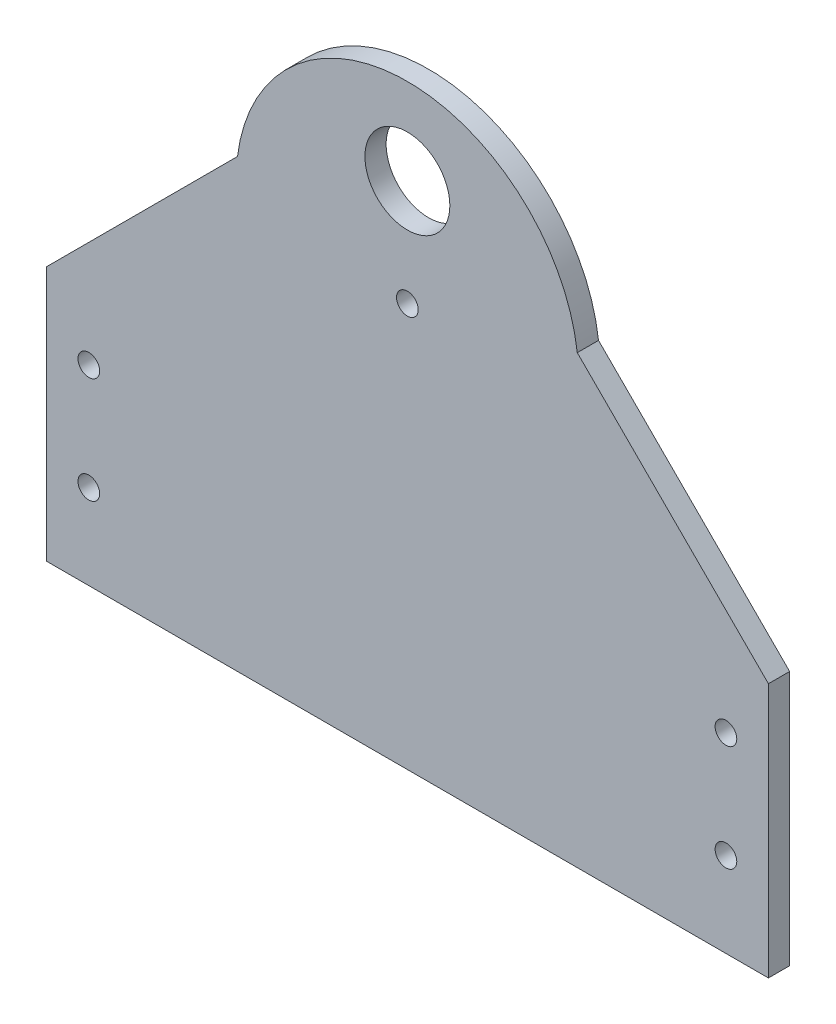
SolidWorks part; units mm, degrees
ref_plane "正面" through (0, 0, 0) normal (0, 0, 1) x (1, 0, 0)
ref_plane "平面" through (0, 0, 0) normal (0, 1, 0) x (1, 0, 0)
ref_plane "右側面" through (0, 0, 0) normal (1, 0, 0) x (0, 0, -1)
sketch "ｽｹｯﾁ1" plane through (0, 0, 0) normal (0, 0, 1) x (1, 0, 0)
  line L0 (-85, -71.4) -> (-85, -11.4)
  line L1 (-85, -11.4) -> (-40, 33.6)
  line L2 (-40, 33.6) -> (40, 33.6) construction
  line L3 (40, 33.6) -> (85, -11.4)
  line L4 (85, -11.4) -> (85, -71.4)
  line L5 (85, -71.4) -> (-85, -71.4)
  line L6 (40, 33.6) -> (-85, -71.4) construction
  line L7 (-40, 33.6) -> (85, -71.4) construction
  line L8 (0, 0) -> (0, -18.9) construction
  line L9 (-75, -61.4) -> (75, -61.4) construction
  line L10 (-75, -61.4) -> (-75, 23.6) construction
  line L11 (-75, 23.6) -> (75, 23.6) construction
  line L12 (75, -61.4) -> (75, 23.6) construction
  line L13 (-75, -61.4) -> (75, 23.6) construction
  line L14 (-75, 23.6) -> (75, -61.4) construction
  line L15 (0, 48.6) -> (0, 0) construction
  circle A0 centre (75, -26.4) radius 2.55
  circle A1 centre (75, -51.4) radius 2.55
  circle A2 centre (-75, -26.4) radius 2.55
  circle A3 centre (-75, -51.4) radius 2.55
  circle A4 centre (0, 23.6) radius 2.55
  arc A5 (-40, 33.6) -> (40, 33.6) centre (0, 28.6) cw
  circle A6 centre (0, 48.6) radius 10
  point P2 (0, 0)
  point P10 (0, -18.9)
  dimension "D9" = 20
  dimension "D13" = 5.1
  dimension "D14" = 5
  dimension "D15" = 20
  dimension "D1" = 170
  dimension "D2" = 45
  dimension "D3" = 45
  dimension "D4" = 80
  dimension "D5" = 60
  dimension "D6" = 10
  dimension "D7" = 10
  dimension "D8" = 10
  dimension "D10" = 25
  dimension "D11" = 20
  dimension "D12" = 25
  dimension "D16" = 15
extrude "ﾎﾞｽ - 押し出し1" add sketch "ｽｹｯﾁ1" along normal blind 5
